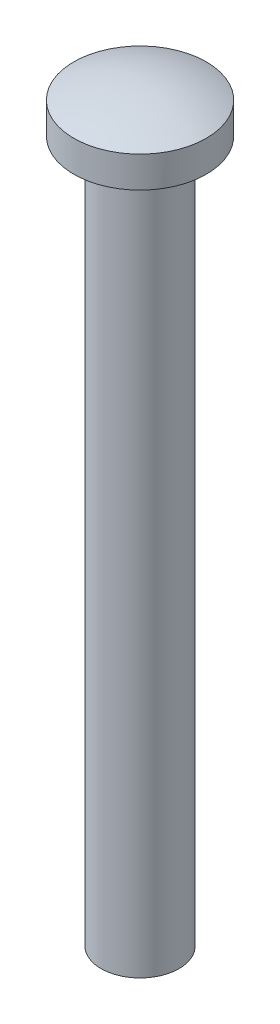
SolidWorks part; units mm, degrees
ref_plane "前基準面" through (0, 0, 0) normal (0, 0, 1) x (1, 0, 0)
ref_plane "上基準面" through (0, 0, 0) normal (0, 1, 0) x (1, 0, 0)
ref_plane "右基準面" through (0, 0, 0) normal (1, 0, 0) x (0, 0, -1)
sketch "草圖1" plane through (0, 0, 0) normal (0, 0, 1) x (1, 0, 0)
  line L0 (0, 0) -> (0, 9.581)
  line L1 (-0.85, 9.4) -> (-0.85, 9)
  line L2 (-0.85, 9) -> (-0.5, 9)
  line L3 (-0.5, 9) -> (-0.5, 0)
  line L4 (-0.5, 0) -> (0, 0)
  arc A0 (0, 9.581) -> (-0.85, 9.4) centre (0, 7.4949) ccw
  dimension "D4" = 2.0862
  dimension "D1" = 0.5
  dimension "D2" = 9
  dimension "D3" = 0.4
  dimension "D5" = 0.85
revolve "旋轉1" add sketch "草圖1" angle 360 about L0
cosmetic thread "裝飾螺紋線1" parameters "D1"=0.8, "D2"=0.711
